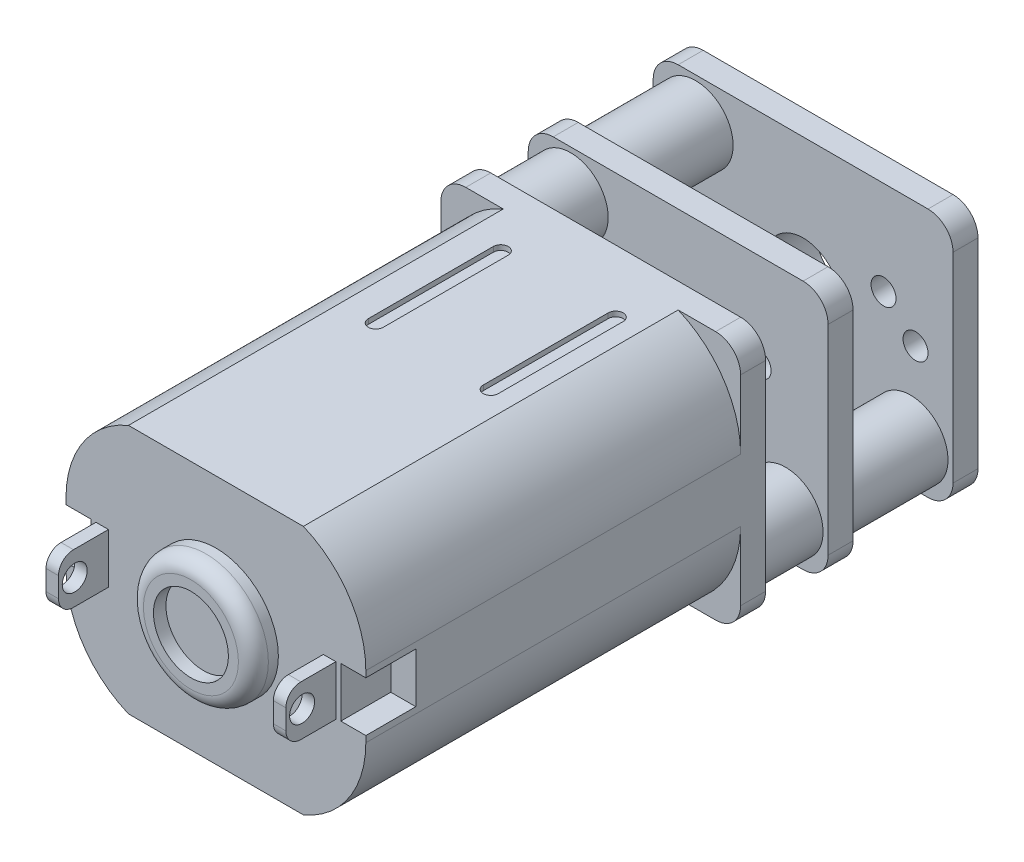
SolidWorks part; units mm, degrees
ref_plane "Front Plane" through (0, 0, 0) normal (0, 0, 1) x (1, 0, 0)
ref_plane "Top Plane" through (0, 0, 0) normal (0, 1, 0) x (1, 0, 0)
ref_plane "Right Plane" through (0, 0, 0) normal (1, 0, 0) x (0, 0, -1)
sketch "Sketch1" plane through (0, 0, 0) normal (0, 0, 1) x (1, 0, 0)
  line L0 (-6, -1.25) -> (-6, 1.25)
  line L1 (3.5, 5) -> (-3.5, 5)
  line L2 (0, 5) -> (0, -5) construction
  line L3 (-6, 0) -> (0, 0) construction
  line L4 (6, -1.25) -> (6, 1.25)
  line L5 (3.5, -5) -> (-3.5, -5)
  arc A0 (-6, 1.25) -> (-3.5, 5) centre (-1.9375, 1.25) cw
  arc A1 (6, 1.25) -> (3.5, 5) centre (1.9375, 1.25) ccw
  arc A2 (6, -1.25) -> (3.5, -5) centre (1.9375, -1.25) cw
  arc A3 (-6, -1.25) -> (-3.5, -5) centre (-1.9375, -1.25) ccw
  point P18 (6, 0)
  dimension "D1" = 5
  dimension "D2" = 1.25
  dimension "D3" = 6
  dimension "D4" = 3.5
extrude "Boss-Extrude1" add sketch "Sketch1" against normal blind 15
sketch "Sketch2" plane through (0, 0, -15) normal (0, 0, -1) x (-1, 0, 0)
  line L1 (6, -5) -> (-6, -5)
  line L2 (6, -5) -> (6, 5)
  line L3 (6, 5) -> (-6, 5)
  line L4 (-6, -5) -> (-6, 5)
  line L5 (6, -5) -> (-6, 5) construction
  line L6 (6, 5) -> (-6, -5) construction
  point P0 (0, 0)
  dimension "D1" = 10
  dimension "D2" = 12
extrude "Boss-Extrude2" add sketch "Sketch2" along normal blind 1
fillet "Fillet1" radius 1 4 edges at (-6, -5, -15.5) (6, -5, -15.5) (-6, 5, -15.5) (6, 5, -15.5)
sketch "Sketch3" plane through (0, 0, -16) normal (0, 0, -1) x (-1, 0, 0)
  circle A0 centre (0, 0) radius 1
  dimension "D1" = 2
extrude "Boss-Extrude3" add sketch "Sketch3" along normal blind 2
sketch "Sketch4" plane through (0, 0, -16) normal (0, 0, -1) x (-1, 0, 0)
  line L0 (-5, -5) -> (5, -5) construction
  line L1 (-6, 4) -> (-6, -4) construction
  line L2 (6, -4) -> (6, 4) construction
  line L3 (5, 5) -> (-5, 5) construction
  circle A0 centre (4.3, 3.3) radius 1.5
  circle A1 centre (-4.3, -3.3) radius 1.5
  dimension "D1" = 3
  dimension "D2" = 3
  dimension "D4" = 1.7
  dimension "D5" = 1.7
  dimension "D6" = 1.7
  dimension "D3" = 1.7
extrude "Boss-Extrude4" add sketch "Sketch4" along normal blind 2.5
sketch "Sketch12" plane through (0, 0, 0) normal (0, 0, 1) x (1, 0, 0)
  circle A0 centre (0, 0) radius 2.5
  dimension "D1" = 5
extrude "Boss-Extrude11" add sketch "Sketch12" along normal blind 1
sketch "Sketch13" plane through (0, 0, 1) normal (0, 0, 1) x (1, 0, 0)
  circle A0 centre (0, 0) radius 1.5
  dimension "D1" = 3
extrude "Cut-Extrude4" cut sketch "Sketch13" against normal blind 0.5
fillet "Fillet5" radius 0.6 1 edges at (2.5, 0, 1)
sketch "Sketch15" plane through (0, 0, 0) normal (0, 0, 1) x (1, 0, 0)
  line L0 (-6, 1.25) -> (-6, -1.25) construction
  line L1 (-6, -1) -> (-5, -1)
  line L2 (-6, -1) -> (-6, 1)
  line L3 (-6, 1) -> (-5, 1)
  line L4 (-5, -1) -> (-5, 1)
  line L5 (6, -1.25) -> (6, 1.25) construction
  line L6 (6, -1) -> (5, -1)
  line L7 (6, -1) -> (6, 1)
  line L8 (6, 1) -> (5, 1)
  line L9 (5, -1) -> (5, 1)
  circle A0 centre (0, 0) radius 1.5 construction
  circle A1 centre (0, 0) radius 1.9 construction
  dimension "D1" = 2
  dimension "D2" = 2
  dimension "D3" = 1
  dimension "D4" = 1
  dimension "D5" = 1
  dimension "D6" = 1
extrude "Cut-Extrude5" cut sketch "Sketch15" against normal blind 2
sketch "Sketch22" plane through (0, 5, 0) normal (0, 1, 0) x (1, 0, 0)
  line L0 (-2.1, 8.5) -> (-2.1, 13.5) construction
  line L1 (-2.4, 8.5) -> (-2.4, 13.5)
  line L2 (-1.8, 8.5) -> (-1.8, 13.5)
  line L3 (2.5, 8.5) -> (2.5, 13.5) construction
  line L4 (2.2, 8.5) -> (2.2, 13.5)
  line L5 (2.8, 8.5) -> (2.8, 13.5)
  line L7 (-5, 16) -> (5, 16) construction
  line L8 (3.5, 15) -> (3.5, 0) construction
  arc A0 (-2.4, 8.5) -> (-1.8, 8.5) centre (-2.1, 8.5) ccw
  arc A1 (-1.8, 13.5) -> (-2.4, 13.5) centre (-2.1, 13.5) ccw
  arc A2 (2.2, 8.5) -> (2.8, 8.5) centre (2.5, 8.5) ccw
  arc A3 (2.8, 13.5) -> (2.2, 13.5) centre (2.5, 13.5) ccw
  point P2 (-2.1, 11)
  point P9 (2.5, 11)
  dimension "D3" = 0.3
  dimension "D4" = 0.3
  dimension "D1" = 5
  dimension "D2" = 5
  dimension "D5" = 4
  dimension "D6" = 5
  dimension "D7" = 5
  dimension "D8" = 0.6
  dimension "D9" = 0.7
extrude "Cut-Extrude6" cut sketch "Sketch22" against normal blind 0.2
sketch "Sketch23" plane through (0, -5, 0) normal (0, -1, 0) x (1, 0, 0)
  line L0 (-2.5, -13.5) -> (-2.5, -8.5) construction
  line L1 (-2.8, -13.5) -> (-2.8, -8.5)
  line L2 (-2.2, -13.5) -> (-2.2, -8.5)
  line L3 (2.5, -13.5) -> (2.5, -8.5) construction
  line L4 (2.2, -13.5) -> (2.2, -8.5)
  line L5 (2.8, -13.5) -> (2.8, -8.5)
  line L6 (5, -16) -> (-5, -16) construction
  line L7 (-3.5, -15) -> (-3.5, 0) construction
  line L8 (3.5, -15) -> (3.5, 0) construction
  arc A0 (-2.8, -13.5) -> (-2.2, -13.5) centre (-2.5, -13.5) ccw
  arc A1 (-2.2, -8.5) -> (-2.8, -8.5) centre (-2.5, -8.5) ccw
  arc A2 (2.2, -13.5) -> (2.8, -13.5) centre (2.5, -13.5) ccw
  arc A3 (2.8, -8.5) -> (2.2, -8.5) centre (2.5, -8.5) ccw
  point P2 (-2.5, -11)
  point P9 (2.5, -11)
  dimension "D3" = 0.3
  dimension "D4" = 0.3
  dimension "D1" = 5
  dimension "D2" = 5
  dimension "D5" = 5
  dimension "D6" = 5
  dimension "D7" = 0.7
  dimension "D8" = 0.7
extrude "Cut-Extrude7" cut sketch "Sketch23" against normal blind 0.2
sketch "Sketch24" plane through (0, 0, -18.5) normal (0, 0, -1) x (-1, 0, 0)
  line L0 (2, -5) -> (2, 1.11)
  line L1 (2, -5) -> (-6, -5)
  line L2 (6, 1.11) -> (6, 5)
  line L3 (6, 5) -> (-6, 5)
  line L4 (-6, -5) -> (-6, 5)
  line L5 (6, -5) -> (-6, 5) construction
  line L6 (6, 5) -> (-6, -5) construction
  line L7 (2, 1.11) -> (6, 1.11)
  point P0 (0, 0)
  dimension "D1" = 12
  dimension "D2" = 10
  dimension "D3" = 4
  dimension "D4" = 6.11
sketch "Sketch31" plane through (0, 0, 0) normal (0, 0, 1) x (1, 0, 0)
  line L0 (-5, -1) -> (-5, 1) construction
  line L1 (-4.8, -1.0086) -> (-4.3, -1.0086)
  line L2 (-4.8, -1.0086) -> (-4.8, 0.9914)
  line L3 (-4.8, 0.9914) -> (-4.3, 0.9914)
  line L4 (-4.3, -1.0086) -> (-4.3, 0.9914)
  line L5 (4.8, -1.0393) -> (4.3, -1.0393)
  line L6 (4.8, -1.0393) -> (4.8, 0.9607)
  line L7 (4.8, 0.9607) -> (4.3, 0.9607)
  line L8 (4.3, -1.0393) -> (4.3, 0.9607)
  line L9 (5, 1) -> (5, -1) construction
  dimension "D1" = 2
  dimension "D2" = 0.5
  dimension "D3" = 0.2
  dimension "D4" = 2
  dimension "D5" = 0.5
  dimension "D6" = 0.2
extrude "Boss-Extrude16" add sketch "Sketch31" along normal blind 2
fillet "Fillet9" radius 0.6 4 edges at (4.55, -1.0393, 2) (4.55, 0.9607, 2) (-4.55, -1.0086, 2) (-4.55, 0.9914, 2)
sketch "Sketch32" plane through (-4.8, 0, 0) normal (-1, 0, 0) x (0, 0, 1)
  line L0 (2, 0.3914) -> (2, -0.4086) construction
  circle A0 centre (1.35, 0) radius 0.5
  dimension "D1" = 1
  dimension "D2" = 0.65
extrude "Cut-Extrude10" cut sketch "Sketch32" against normal blind 2
sketch "Sketch33" plane through (4.8, 0, 0) normal (1, 0, 0) x (0, 0, -1)
  line L0 (-2, -0.4393) -> (-2, 0.3607) construction
  circle A0 centre (-1.35, 0) radius 0.5
  dimension "D1" = 1
  dimension "D2" = 0.65
extrude "Cut-Extrude11" cut sketch "Sketch33" against normal blind 2
extrude "Boss-Extrude17" add sketch "Sketch24" along normal blind 1
fillet "Fillet10" radius 1 4 edges at (-6, 5, -19) (6, 5, -19) (6, -5, -19) (-2, -5, -19)
sketch "Sketch34" plane through (0, 0, -19.5) normal (0, 0, -1) x (-1, 0, 0)
  circle A0 centre (-4.3, -3.3) radius 1.5
  circle A1 centre (4.3, 3.3) radius 1.5
extrude "Boss-Extrude18" add sketch "Sketch34" along normal blind 4
sketch "Sketch35" plane through (0, 0, -23.5) normal (0, 0, -1) x (-1, 0, 0)
  line L1 (6, -5) -> (-6, -5)
  line L2 (6, -5) -> (6, 5)
  line L3 (6, 5) -> (-6, 5)
  line L4 (-6, -5) -> (-6, 5)
  line L5 (6, -5) -> (-6, 5) construction
  line L6 (6, 5) -> (-6, -5) construction
  point P0 (0, 0)
  dimension "D1" = 10
  dimension "D2" = 12
extrude "Boss-Extrude19" add sketch "Sketch35" along normal blind 1
sketch "Sketch36" plane through (0, 0, -24.5) normal (0, 0, -1) x (-1, 0, 0)
  circle A0 centre (0, 0) radius 2
  dimension "D1" = 4
extrude "Boss-Extrude20" add sketch "Sketch36" along normal blind 1
sketch "Sketch37" plane through (0, 0, -25.5) normal (0, 0, -1) x (-1, 0, 0)
  circle A0 centre (0, 0) radius 1.5
  dimension "D1" = 3
extrude "Cut-Extrude12" cut sketch "Sketch37" against normal blind 2
fillet "Fillet11" radius 1 4 edges at (-6, -5, -24) (-6, 5, -24) (6, 5, -24) (6, -5, -24)
sketch "Sketch38" plane through (0, 0, -24.5) normal (0, 0, -1) x (-1, 0, 0)
  circle A0 centre (-4.5, 0) radius 0.5
  circle A1 centre (4.5, 0) radius 0.5
  circle A2 centre (0, 0) radius 1.5 construction
  dimension "D1" = 1
  dimension "D2" = 1
  dimension "D3" = 9
  dimension "D4" = 4.5
extrude "Cut-Extrude13" cut sketch "Sketch38" against normal blind 2
sketch "Sketch39" plane through (0, 0, -24.5) normal (0, 0, -1) x (-1, 0, 0)
  circle A0 centre (-4.3, -3.3) radius 0.75
  circle A1 centre (4.3, 3.3) radius 0.75
  dimension "D1" = 1.5
  dimension "D2" = 1.5
extrude "Cut-Extrude14" cut sketch "Sketch39" against normal blind 9.3
chamfer "Chamfer1" distance 0.3 angle 45 2 edges at (-5.05, 3.3, -24.5) (3.55, -3.3, -24.5)
sketch "Sketch40" plane through (0, 0, -19.5) normal (0, 0, -1) x (-1, 0, 0)
  circle A0 centre (0, 0) radius 0.5
  dimension "D1" = 1
extrude "Cut-Extrude15" cut sketch "Sketch40" against normal blind 1
sketch "Sketch41" plane through (0, 0, -24.5) normal (0, 0, -1) x (-1, 0, 0)
  line L0 (6, -4) -> (6, 4) construction
  line L1 (-5, -5) -> (5, -5) construction
  line L2 (-6, 4) -> (-6, -4) construction
  line L3 (5, 5) -> (-5, 5) construction
  circle A0 centre (3.22, -1.25) radius 0.5
  circle A1 centre (-3.22, 1.25) radius 0.5
  dimension "D1" = 1
  dimension "D2" = 2.78
  dimension "D3" = 3.75
  dimension "D4" = 1
  dimension "D5" = 2.78
  dimension "D6" = 3.75
extrude "Cut-Extrude16" cut sketch "Sketch41" against normal blind 1
sketch "Sketch42" plane through (0, 0, -19.5) normal (0, 0, -1) x (-1, 0, 0)
  line L0 (5, 5) -> (-5, 5) construction
  line L1 (-6, 4) -> (-6, -4) construction
  circle A0 centre (-3.22, 1.25) radius 0.5
  dimension "D1" = 1
  dimension "D2" = 3.75
  dimension "D3" = 2.78
extrude "Cut-Extrude17" cut sketch "Sketch42" against normal blind 1
sketch "Sketch43" plane through (0, 0, -16) normal (0, 0, -1) x (-1, 0, 0)
  line L0 (-5, -5) -> (5, -5) construction
  line L1 (6, -4) -> (6, 4) construction
  circle A0 centre (3.22, -1.25) radius 0.5
  dimension "D1" = 1
  dimension "D2" = 3.75
  dimension "D3" = 2.78
extrude "Cut-Extrude18" cut sketch "Sketch43" against normal blind 1
